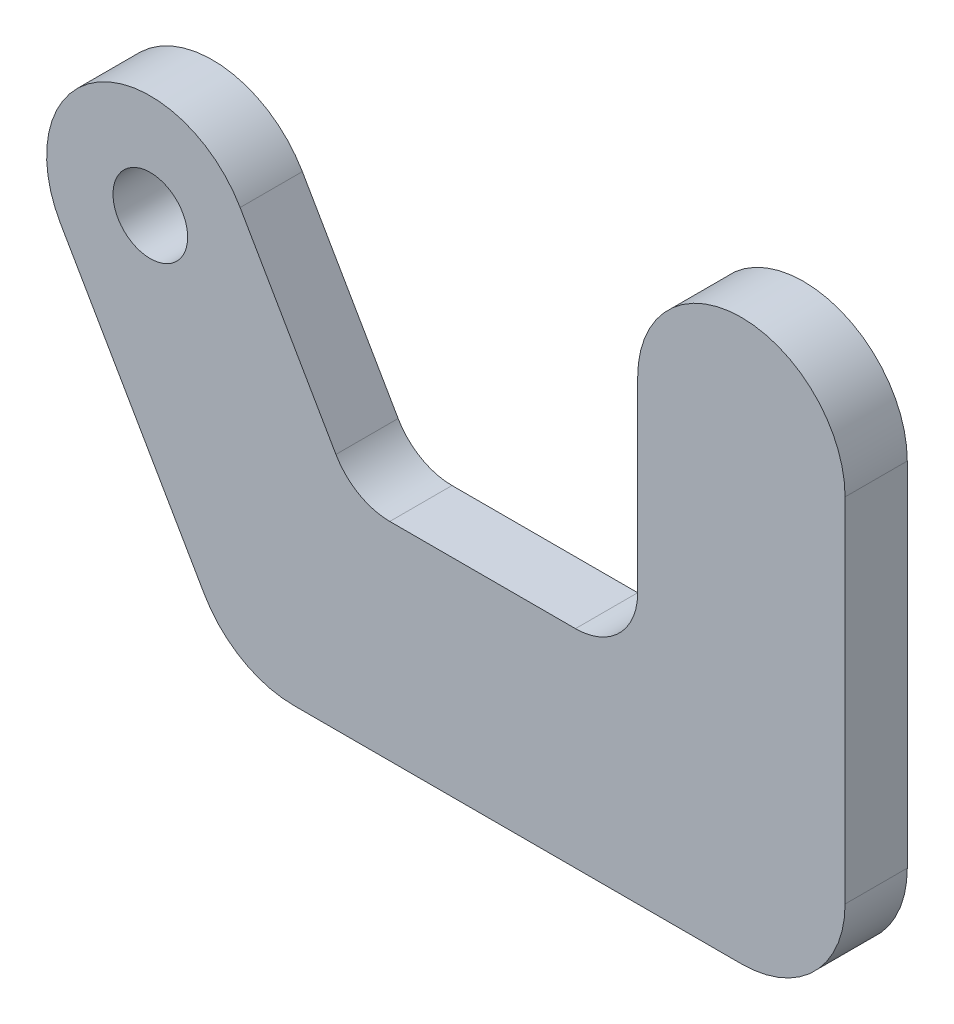
SolidWorks part; units mm, degrees
ref_plane "Front Plane" through (0, 0, 0) normal (0, 0, 1) x (1, 0, 0)
ref_plane "Top Plane" through (0, 0, 0) normal (0, 1, 0) x (1, 0, 0)
ref_plane "Right Plane" through (0, 0, 0) normal (1, 0, 0) x (0, 0, -1)
sketch "Sketch1" plane through (0, 0, 0) normal (0, 0, 1) x (1, 0, 0)
  line L0 (0, 0) -> (6.9282, -12) construction
  line L1 (6.9282, -12) -> (28.5, -12) construction
  line L2 (28.5, -12) -> (28.5, 5) construction
  line L3 (-4.3301, -2.5) -> (4.0415, -17)
  line L4 (4.0415, -17) -> (33.5, -17)
  line L5 (33.5, -17) -> (33.5, 5)
  line L6 (4.3301, 2.5) -> (9.815, -7)
  line L7 (9.815, -7) -> (23.5, -7)
  line L8 (23.5, -7) -> (23.5, 5)
  line L9 (23.5, -7) -> (23.5, 5) construction
  circle A0 centre (0, 0) radius 1.8
  arc A2 (33.5, 5) -> (23.5, 5) centre (28.5, 5) ccw
  arc A3 (4.3301, 2.5) -> (-4.3301, -2.5) centre (0, 0) ccw
  point P14 (23.5, 0.9155)
  point P16 (0, 0)
  dimension "D1" = 3.6
  dimension "D2" = 28.5
  dimension "D3" = 12
  dimension "D6" = 120
  dimension "D7" = 22
  dimension "D4" = 5
  dimension "D5" = 5
extrude "Boss-Extrude1" add sketch "Sketch1" along normal blind 3 contours L6 A3 L3 L4 L5 A2 L8 L7 A0
fillet "Fillet2" radius 5 2 edges at (33.5, -17, 1.5) (4.0415, -17, 1.5)
fillet "Fillet3" radius 3 2 edges at (9.815, -7, 1.5) (23.5, -7, 1.5)
